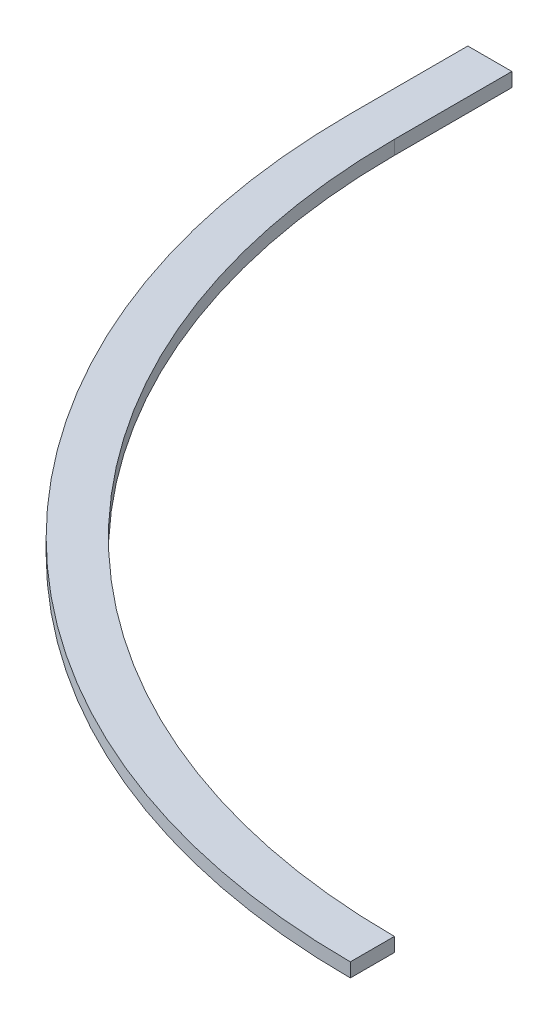
SolidWorks part; units mm, degrees
material "Pine"
ref_plane "Front Plane" through (0, 0, 0) normal (0, 0, 1) x (1, 0, 0)
ref_plane "Top Plane" through (0, 0, 0) normal (0, 1, 0) x (1, 0, 0)
ref_plane "Right Plane" through (0, 0, 0) normal (1, 0, 0) x (0, 0, -1)
sketch "Sketch2" plane through (0, 0, 0) normal (0, 1, 0) x (1, 0, 0)
  line L0 (0, 0) -> (-500, 0)
  line L1 (0, 0) -> (0, -500)
  circle A0 centre (0, 0) radius 500
  circle A1 centre (0, 0) radius 470
  dimension "D1" = 1000
  dimension "D2" = 30
extrude "Boss-Extrude1" add sketch "Sketch2" along normal blind 9.525 contours A1 L0 A0 L1
sketch "Sketch3" plane through (0, 0, 0) normal (0, 0, -1) x (-1, 0, 0)
  line L8 (470, 0) -> (500, 0)
  line L9 (500, 0) -> (500, 9.525)
  line L10 (500, 9.525) -> (470, 9.525)
  line L11 (470, 9.525) -> (470, 0)
  line L12 (470, 0) -> (500, 0)
  line L13 (500, 0) -> (500, 9.525)
  line L14 (500, 9.525) -> (470, 9.525)
  line L15 (470, 9.525) -> (470, 0)
  dimension "D1" = 0
extrude "Boss-Extrude2" add sketch "Sketch3" along normal blind 80
sketch "Sketch4" plane through (0, 9.525, 0) normal (0, 1, 0) x (1, 0, 0)
  line L1 (-500, 80) -> (0, 80) construction
  line L2 (-500, 80) -> (-500, -500) construction
  line L3 (-500, -500) -> (0, -500) construction
  line L4 (0, 80) -> (0, -500) construction
  line L5 (-500, 80) -> (-195.2, 80) construction
  line L6 (-500, 80) -> (-500, -326.4) construction
  line L7 (-500, -326.4) -> (-195.2, -326.4) construction
  line L8 (-195.2, 80) -> (-195.2, -326.4) construction
  line L9 (0, -500) -> (-406.4, -500) construction
  line L10 (0, -500) -> (0, -195.2) construction
  line L11 (0, -195.2) -> (-406.4, -195.2) construction
  line L12 (-406.4, -500) -> (-406.4, -195.2) construction
  dimension "D1" = 304.8
  dimension "D2" = 406.4
  dimension "D3" = 304.8
  dimension "D4" = 406.4
